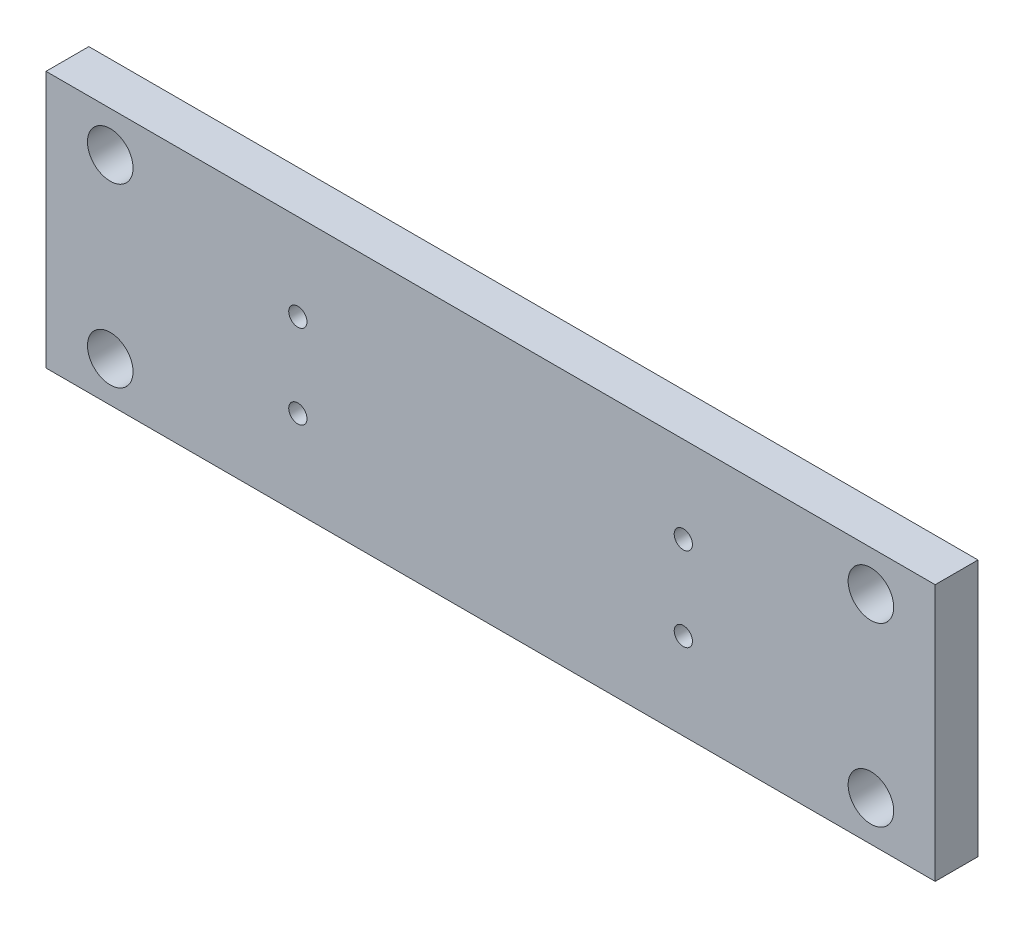
SolidWorks part; units mm, degrees
ref_plane "Front" through (0, 0, 0) normal (0, 0, 1) x (1, 0, 0)
ref_plane "Top" through (0, 0, 0) normal (0, 1, 0) x (1, 0, 0)
ref_plane "Right" through (0, 0, 0) normal (1, 0, 0) x (0, 0, -1)
sketch "Sketch1" plane through (0, 0, 0) normal (0, 0, 1) x (1, 0, 0)
  line L1 (-65.913, -19.05) -> (65.913, -19.05)
  line L2 (-65.913, -19.05) -> (-65.913, 19.05)
  line L3 (-65.913, 19.05) -> (65.913, 19.05)
  line L4 (65.913, -19.05) -> (65.913, 19.05)
  line L5 (-65.913, -19.05) -> (65.913, 19.05) construction
  line L6 (-65.913, 19.05) -> (65.913, -19.05) construction
  point P0 (0, 0)
  dimension "D1" = 131.826
  dimension "D2" = 38.1
extrude "Boss-Extrude1" add sketch "Sketch1" along normal blind 6.35
sketch "Sketch2" plane through (0, 0, 6.35) normal (0, 0, 1) x (1, 0, 0)
  line L0 (-56.388, 19.05) -> (-56.388, 13.081) construction
  line L1 (65.913, 19.05) -> (-65.913, 19.05) construction
  line L2 (-56.388, 13.081) -> (-56.388, -13.081) construction
  line L3 (-56.388, -13.081) -> (-56.388, -19.05) construction
  line L4 (-65.913, -19.05) -> (65.913, -19.05) construction
  line L5 (-65.913, 19.05) -> (-65.913, -19.05) construction
  line L6 (-28.575, 19.05) -> (-28.575, 6.2103) construction
  line L7 (-28.575, 6.2103) -> (-28.575, -6.2103) construction
  line L8 (-28.575, -6.2103) -> (-28.575, -19.05) construction
  dimension "D1" = 12.4206
  dimension "D2" = 26.162
  dimension "D3" = 9.525
  dimension "D4" = 28.575
hole_wizard "1/4 Clearance Hole1" positions "Sketch4" profile "Sketch3" hole size "1/4" standard "ANSI Inch" end condition through all
sketch "Sketch4" plane through (0, 0, 6.35) normal (0, 0, 1) x (1, 0, 0)
  point P0 (-56.388, 13.081)
  point P3 (-56.388, -13.081)
sketch "Sketch3" plane through (-56.388, 13.081, 6.35) normal (1, 0, 0) x (0, -1, 0)
  line L0 (0, 0) -> (0, 6.35)
  line L1 (0, 6.35) -> (3.3782, 6.35)
  line L2 (3.3782, 6.35) -> (3.3782, 0)
  line L5 (3.3782, 0) -> (0, 0)
  line L11 (0, -6.35) -> (0, 107.95) construction
  dimension "Thru Hole Dia." = 6.7564
  dimension "Thru Hole Depth" = 6.35
hole_wizard "#6-32 Tapped Hole1" positions "Sketch6" profile "Sketch5" tap size "#6-32" standard "ANSI Inch" end condition through all
sketch "Sketch6" plane through (0, 0, 6.35) normal (0, 0, 1) x (1, 0, 0)
  point P0 (-28.575, 6.2103)
  point P3 (-28.575, -6.2103)
sketch "Sketch5" plane through (-28.575, 6.2103, 6.35) normal (1, 0, 0) x (0, -1, 0)
  line L0 (0, 0) -> (0, 6.35)
  line L1 (0, 6.35) -> (1.3525, 6.35)
  line L2 (1.3525, 6.35) -> (1.3525, 0)
  line L5 (1.3525, 0) -> (0, 0)
  line L11 (0, -6.35) -> (0, 107.95) construction
  dimension "Thread Major Dia." = 2.7051
  dimension "Thru Tap Drill Depth" = 6.35
mirror "Mirror1" about plane through (0, 0, 0) normal (1, 0, 0) of "#6-32 Tapped Hole1", "1/4 Clearance Hole1"
